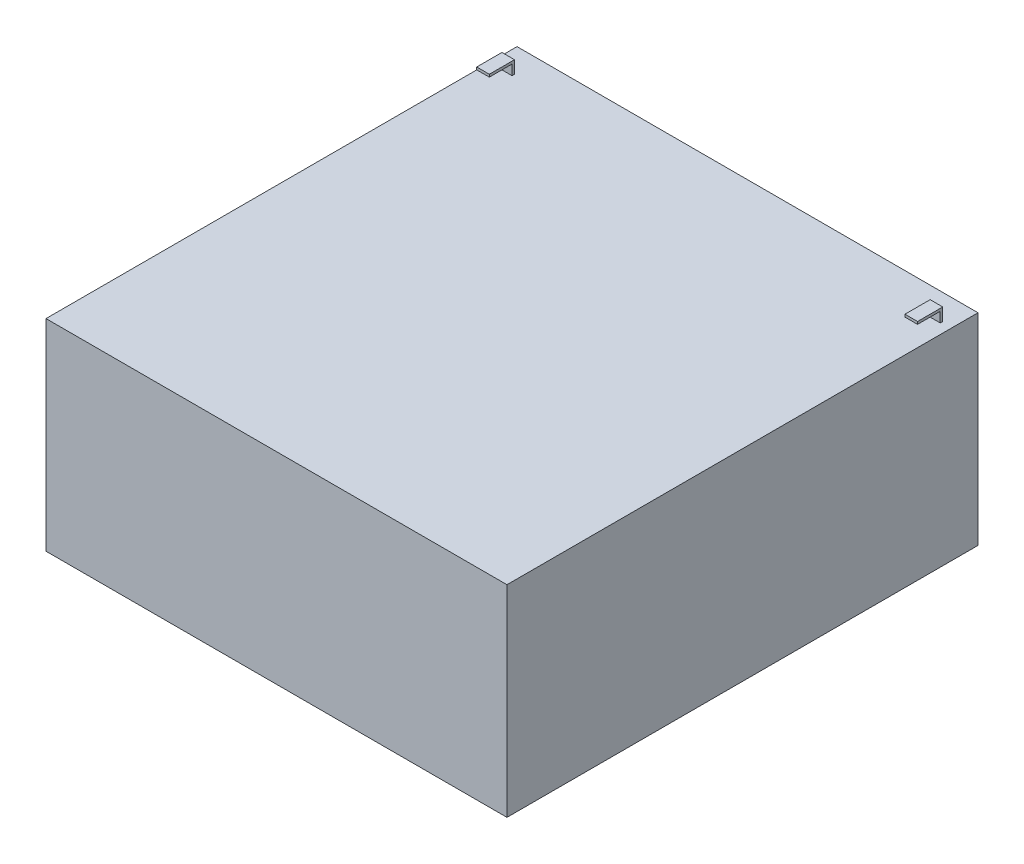
SolidWorks part; units mm, degrees
ref_plane "前视基准面" through (0, 0, 0) normal (0, 0, 1) x (1, 0, 0)
ref_plane "上视基准面" through (0, 0, 0) normal (0, 1, 0) x (1, 0, 0)
ref_plane "右视基准面" through (0, 0, 0) normal (1, 0, 0) x (0, 0, -1)
sketch "草图1" plane through (0, 0, 0) normal (0, 1, 0) x (1, 0, 0)
  line L1 (0, 0) -> (183, 0)
  line L2 (0, 0) -> (0, 187)
  line L3 (0, 187) -> (183, 187)
  line L4 (183, 0) -> (183, 187)
  dimension "D1" = 187
  dimension "D2" = 183
extrude "拉伸1" add sketch "草图1" along normal blind 80
sketch "草图3" plane through (0, 80, 0) normal (0, 1, 0) x (-1, 0, 0)
  line L0 (-183, -187) -> (0, -187) construction
  line L1 (-4, -177) -> (-9, -177)
  line L2 (-4, -177) -> (-4, -176)
  line L3 (-4, -176) -> (-9, -176)
  line L4 (-9, -177) -> (-9, -176)
  line L5 (0, -187) -> (0, 0) construction
  dimension "D1" = 10
  dimension "D2" = 4
  dimension "D3" = 5
  dimension "D4" = 1
ref_plane "基准面1" through (4, 0, 0) normal (-1, 0, 0) x (0, 0, 1)
sketch "草图4" plane through (4, 0, 0) normal (-1, 0, 0) x (0, 0, 1)
  line L0 (-177, 80) -> (-177, 85)
  line L1 (-177, 85) -> (-167, 85)
  dimension "D1" = 10
  dimension "D2" = 5
sweep "扫描1" add profiles "草图3" path "草图4"
ref_plane "基准面2" through (91.5, 0, 0) normal (-1, 0, 0) x (0, 0, 1)
mirror "镜向2" about plane through (91.5, 0, 0) normal (-1, 0, 0) of "扫描1"
